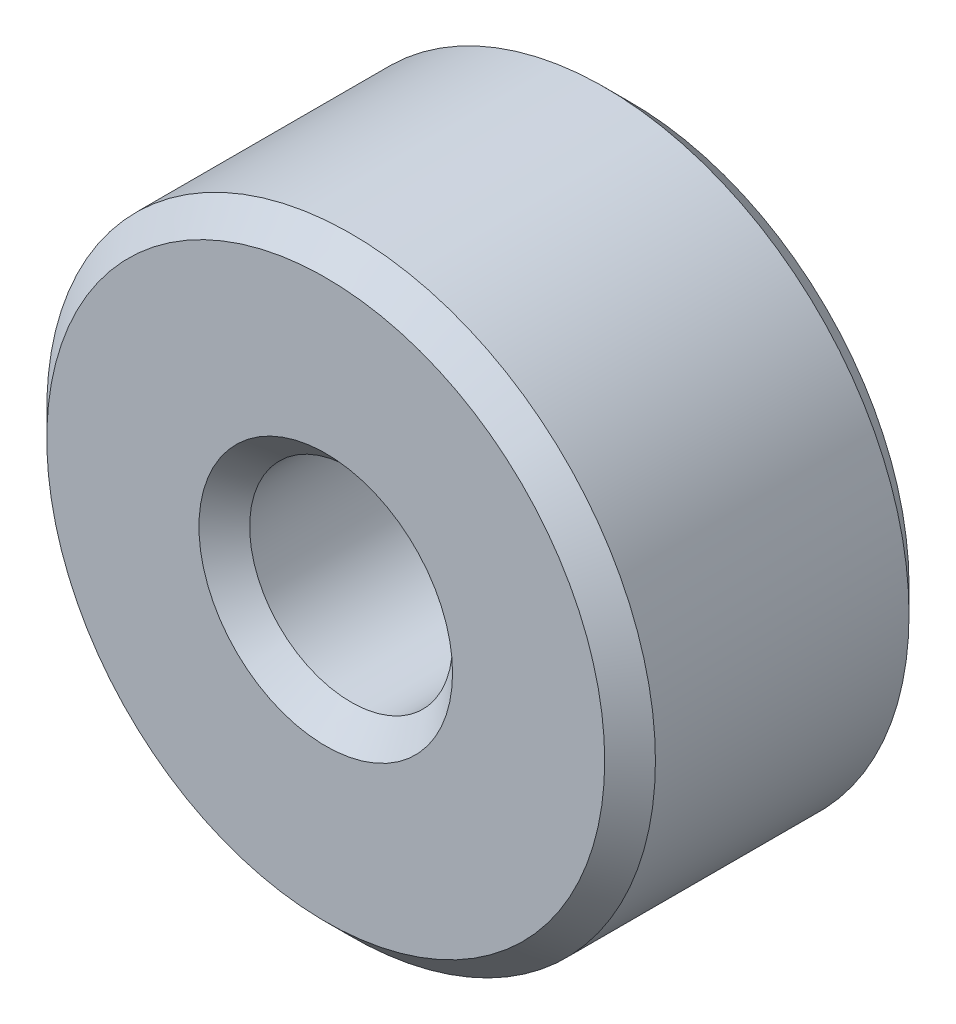
SolidWorks part; units mm, degrees
ref_plane "Front Plane" through (0, 0, 0) normal (0, 0, 1) x (1, 0, 0)
ref_plane "Top Plane" through (0, 0, 0) normal (0, 1, 0) x (1, 0, 0)
ref_plane "Right Plane" through (0, 0, 0) normal (1, 0, 0) x (0, 0, -1)
sketch "Sketch1" plane through (0, 0, 0) normal (0, 0, 1) x (1, 0, 0)
  circle A0 centre (0, 0) radius 1
  dimension "D1" = 2
extrude "Extrude-Thin1" add sketch "Sketch1" along normal blind 3 thin
chamfer "Chamfer1" distance 0.25 angle 45 4 edges at (1, 0, 3) (3, 0, 3) (1, 0, 0) (3, 0, 0)
